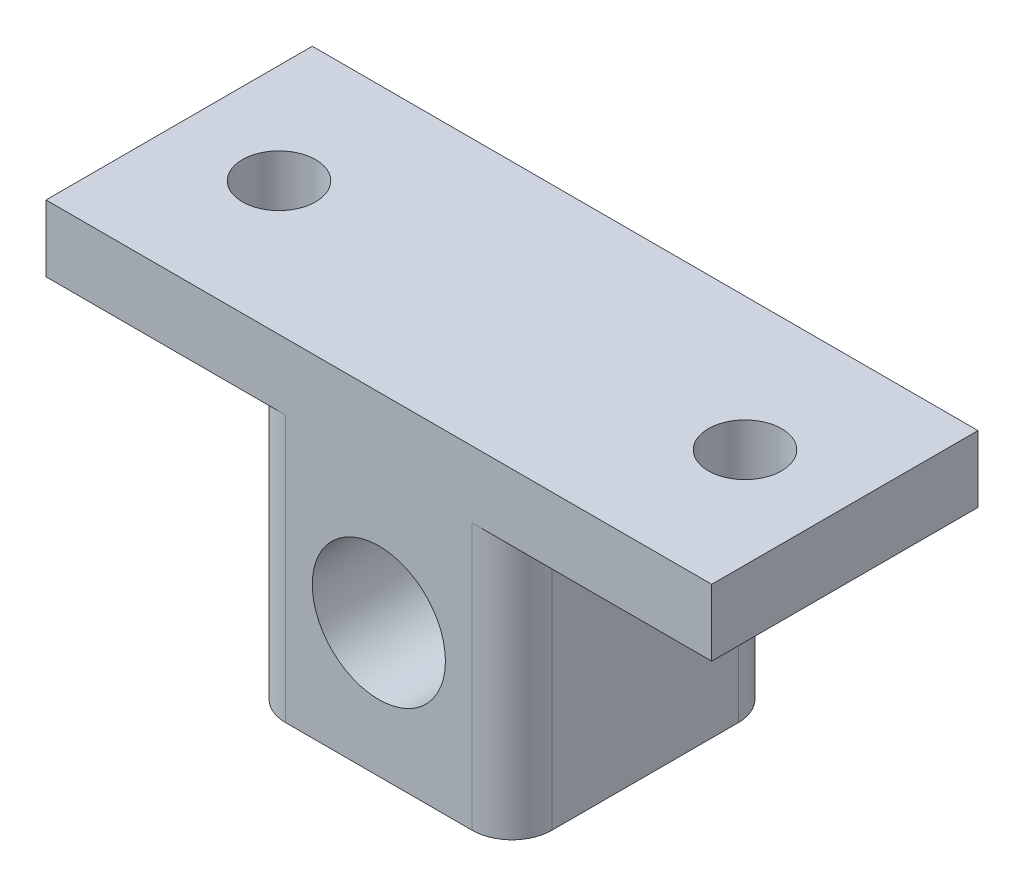
SolidWorks part; units mm, degrees
material "3.3547 (EN-AW 5083)"
ref_plane "Ebene vorne" through (0, 0, 0) normal (0, 0, 1) x (1, 0, 0)
ref_plane "Ebene oben" through (0, 0, 0) normal (0, 1, 0) x (1, 0, 0)
ref_plane "Ebene rechts" through (0, 0, 0) normal (1, 0, 0) x (0, 0, -1)
sketch "Skizze1" plane through (0, 0, 0) normal (0, 0, 1) x (1, 0, 0)
  line L0 (-34.4384, 0) -> (-34.4384, 20)
  line L1 (-34.4384, 20) -> (-49.4384, 20)
  line L2 (-49.4384, 20) -> (-49.4384, 25)
  line L3 (-49.4384, 25) -> (-24.4384, 25)
  line L4 (-34.4384, 0) -> (-24.4384, 0)
  line L5 (-24.4384, 25) -> (-24.4384, 0) construction
  line L6 (-24.4384, 25) -> (0.5616, 25)
  line L7 (0.5616, 25) -> (0.5616, 20)
  line L8 (0.5616, 20) -> (-14.4384, 20)
  line L9 (-14.4384, 20) -> (-14.4384, 0)
  line L10 (-14.4384, 0) -> (-24.4384, 0)
  dimension "D1" = 25
  dimension "D2" = 10
  dimension "D3" = 15
  dimension "D4" = 5
  dimension "D5" = 20
  dimension "D6" = 25
  dimension "D7" = 15
extrude "Aufsatz-Linear austragen1" add sketch "Skizze1" along normal blind 20
sketch "Skizze2" plane through (0, 0, 20) normal (0, 0, 1) x (1, 0, 0)
  circle A0 centre (-24.4384, 10) radius 5
extrude "Schnitt-Linear austragen1" cut sketch "Skizze2" against normal blind 20
sketch "Skizze3" plane through (0, 25, 0) normal (0, 1, 0) x (1, 0, 0)
  line L0 (-49.4384, -20) -> (-49.4384, 0) construction
  line L1 (0.5616, -20) -> (0.5616, 0) construction
  circle A0 centre (-41.9384, -10) radius 2.75
  circle A1 centre (-6.9384, -10) radius 2.75
  dimension "D1" = 7.5
  dimension "D2" = 7.5
extrude "Schnitt-Linear austragen2" cut sketch "Skizze3" against normal blind 20
fillet "Verrundung1" radius 3 4 edges at (-34.4384, 10, 0) (-14.4384, 10, 0) (-34.4384, 10, 20) (-14.4384, 10, 20)
sketch "Skizze4" plane through (0, 0, 20) normal (0, 0, 1) x (1, 0, 0)
  line L2 (-34.4384, 20) -> (-34.4384, 0)
  line L3 (-34.4384, 0) -> (-14.4384, 0)
  line L4 (-14.4384, 0) -> (-14.4384, 20)
  line L5 (-34.4384, 20) -> (-49.4384, 20)
  line L6 (-49.4384, 20) -> (-49.4384, 25)
  line L7 (-49.4384, 25) -> (0.5616, 25)
  line L8 (0.5616, 25) -> (0.5616, 20)
  line L9 (0.5616, 20) -> (-14.4384, 20)
  line L10 (-24.4384, 10) -> (-29.4384, 10) construction
  line L11 (-29.4384, 10) -> (-24.4384, 5) construction
  line L12 (-24.4384, 5) -> (-24.4384, 10) construction
  line L13 (25.5616, 20) -> (25.5616, 0)
  line L14 (25.5616, 0) -> (45.5616, 0)
  line L15 (45.5616, 0) -> (45.5616, 20)
  line L16 (25.5616, 20) -> (10.5616, 20)
  line L17 (10.5616, 20) -> (10.5616, 25)
  line L18 (10.5616, 25) -> (60.5616, 25)
  line L19 (60.5616, 25) -> (60.5616, 20)
  line L20 (60.5616, 20) -> (45.5616, 20)
  line L21 (35.5616, 10) -> (30.5616, 10) construction
  line L22 (30.5616, 10) -> (35.5616, 5) construction
  line L23 (35.5616, 5) -> (35.5616, 10) construction
  circle A0 centre (-24.4384, 10) radius 5 construction
  circle A1 centre (-24.4384, 10) radius 5
  circle A2 centre (35.5616, 10) radius 5
  point P25 (-24.4384, 10)
  point P37 (35.5616, 10)
